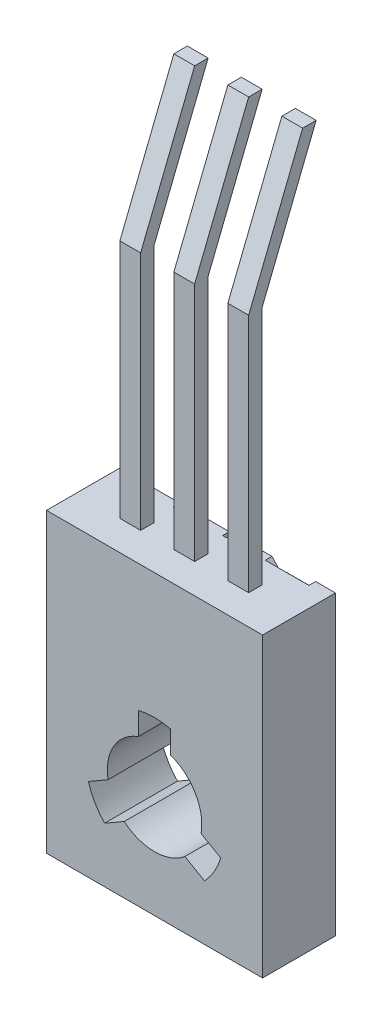
SolidWorks part; units mm, degrees
ref_plane "Front Plane" through (0, 0, 0) normal (0, 0, 1) x (1, 0, 0)
ref_plane "Top Plane" through (0, 0, 0) normal (0, 1, 0) x (1, 0, 0)
ref_plane "Right Plane" through (0, 0, 0) normal (1, 0, 0) x (0, 0, -1)
sketch "Sketch1" plane through (0, 0, 0) normal (0, 0, 1) x (1, 0, 0)
  line L1 (-4, 5.5) -> (4, 5.5)
  line L2 (-4, 5.5) -> (-4, -5.5)
  line L3 (-4, -5.5) -> (4, -5.5)
  line L4 (4, 5.5) -> (4, -5.5)
  line L5 (-4, 5.5) -> (4, -5.5) construction
  line L6 (-4, -5.5) -> (4, 5.5) construction
  circle A0 centre (0, -1.7) radius 2.555
  point P0 (0, 0)
  dimension "D3" = 5.11
  dimension "D1" = 11
  dimension "D2" = 8
  dimension "D4" = 3.8
extrude "Boss-Extrude1" add sketch "Sketch1" along normal mid plane 2.7
sketch "Sketch2" plane through (0, 5.5, 0) normal (0, 1, 0) x (1, 0, 0)
  line L0 (0, 0.8819) -> (0, -0.7814) construction
  line L1 (-0.385, 0.25) -> (0.385, 0.25)
  line L2 (-0.385, 0.25) -> (-0.385, -0.25)
  line L3 (-0.385, -0.25) -> (0.385, -0.25)
  line L4 (0.385, 0.25) -> (0.385, -0.25)
  line L5 (-0.385, 0.25) -> (0.385, -0.25) construction
  line L6 (-0.385, -0.25) -> (0.385, 0.25) construction
  line L7 (-2.385, 0.25) -> (-1.615, 0.25)
  line L8 (-2.385, 0.25) -> (-2.385, -0.25)
  line L9 (-2.385, -0.25) -> (-1.615, -0.25)
  line L10 (-1.615, 0.25) -> (-1.615, -0.25)
  line L11 (-2.385, 0.25) -> (-1.615, -0.25) construction
  line L12 (-2.385, -0.25) -> (-1.615, 0.25) construction
  line L13 (2.385, -0.25) -> (1.615, -0.25)
  line L14 (1.615, 0.25) -> (1.615, -0.25)
  line L15 (2.385, 0.25) -> (1.615, 0.25)
  line L16 (2.385, 0.25) -> (2.385, -0.25)
  point P0 (0, 0)
  point P7 (-2, 0)
  dimension "D1" = 0.5
  dimension "D2" = 0.77
  dimension "D3" = 0.77
  dimension "D4" = 0.5
  dimension "D5" = 2
extrude "Boss-Extrude2" add sketch "Sketch2" along normal blind 8.9
sketch "Sketch4" plane through (0, 0, 1.35) normal (0, 0, 1) x (1, 0, 0)
  line L0 (0, 0.8936) -> (0, -1.7) construction
  line L3 (-0.6, 0.8232) -> (-0.6, -0.0561)
  line L4 (0.6, 0.8232) -> (0.6, -0.0561)
  line L5 (2.4852, -2.442) -> (1.7237, -2.0023)
  line L6 (1.8852, -3.4812) -> (1.1237, -3.0416)
  line L7 (-1.8852, -3.4812) -> (-1.1237, -3.0416)
  line L8 (-2.4852, -2.442) -> (-1.7237, -2.0023)
  arc A0 (-1.1237, -3.0416) -> (1.1237, -3.0416) centre (0, -1.7) ccw
  arc A1 (-1.8852, -3.4812) -> (1.8852, -3.4812) centre (0, -1.7) ccw
  arc A2 (-0.6, -0.0561) -> (-1.7237, -2.0023) centre (0, -1.7) ccw
  arc A3 (-0.6, 0.8232) -> (-2.4852, -2.442) centre (0, -1.7) ccw
  arc A4 (1.7237, -2.0023) -> (0.6, -0.0561) centre (0, -1.7) ccw
  arc A5 (2.4852, -2.442) -> (0.6, 0.8232) centre (0, -1.7) ccw
  point P22 (0, -1.7)
  dimension "D1" = 3.5
  dimension "D2" = 0.6
  dimension "D3" = 3
extrude "Boss-Extrude3" add sketch "Sketch4" against normal up to surface (2.7 mm away) up to face at (0, 0, -1.35)
sketch "Sketch5" plane through (0, 0, -1.35) normal (0, 0, -1) x (-1, 0, 0)
  text T0 "B772" font "Century Gothic" height in points 9
extrude "Cut-Extrude1" cut sketch "Sketch5" against normal blind 0.25
sketch "Sketch6" plane through (0, 14.4, 0) normal (0, 1, 0) x (1, 0, 0)
  line L0 (2.385, -0.25) -> (2.385, 0.25) construction
  line L1 (2.385, 0.25) -> (1.615, 0.25) construction
  line L2 (1.615, 0.25) -> (1.615, -0.25) construction
  line L3 (1.615, -0.25) -> (2.385, -0.25) construction
  line L4 (0.385, -0.25) -> (0.385, 0.25) construction
  line L5 (0.385, 0.25) -> (-0.385, 0.25) construction
  line L6 (-0.385, 0.25) -> (-0.385, -0.25) construction
  line L7 (-0.385, -0.25) -> (0.385, -0.25) construction
  line L8 (-1.615, -0.25) -> (-1.615, 0.25) construction
  line L9 (-1.615, 0.25) -> (-2.385, 0.25) construction
  line L10 (-2.385, 0.25) -> (-2.385, -0.25) construction
  line L11 (-2.385, -0.25) -> (-1.615, -0.25) construction
  line L12 (2.385, -0.25) -> (2.385, 0.25)
  line L13 (2.385, 0.25) -> (1.615, 0.25)
  line L14 (1.615, 0.25) -> (1.615, -0.25)
  line L15 (1.615, -0.25) -> (2.385, -0.25)
  line L16 (0.385, -0.25) -> (0.385, 0.25)
  line L17 (0.385, 0.25) -> (-0.385, 0.25)
  line L18 (-0.385, 0.25) -> (-0.385, -0.25)
  line L19 (-0.385, -0.25) -> (0.385, -0.25)
  line L20 (-1.615, -0.25) -> (-1.615, 0.25)
  line L21 (-1.615, 0.25) -> (-2.385, 0.25)
  line L22 (-2.385, 0.25) -> (-2.385, -0.25)
  line L23 (-2.385, -0.25) -> (-1.615, -0.25)
sketch "Sketch7" plane through (0, 0, 0) normal (1, 0, 0) x (0, 0, -1)
  line L0 (0, 14.4) -> (2, 19.4)
  line L1 (0.25, 14.4) -> (-0.25, 14.4) construction
  line L3 (0, 14.4) -> (0, 19.4) construction
  point P4 (0, 0)
  dimension "D1" = 2
  dimension "D2" = 5
sweep "Sweep1" add profiles "Sketch6" path "Sketch7"
